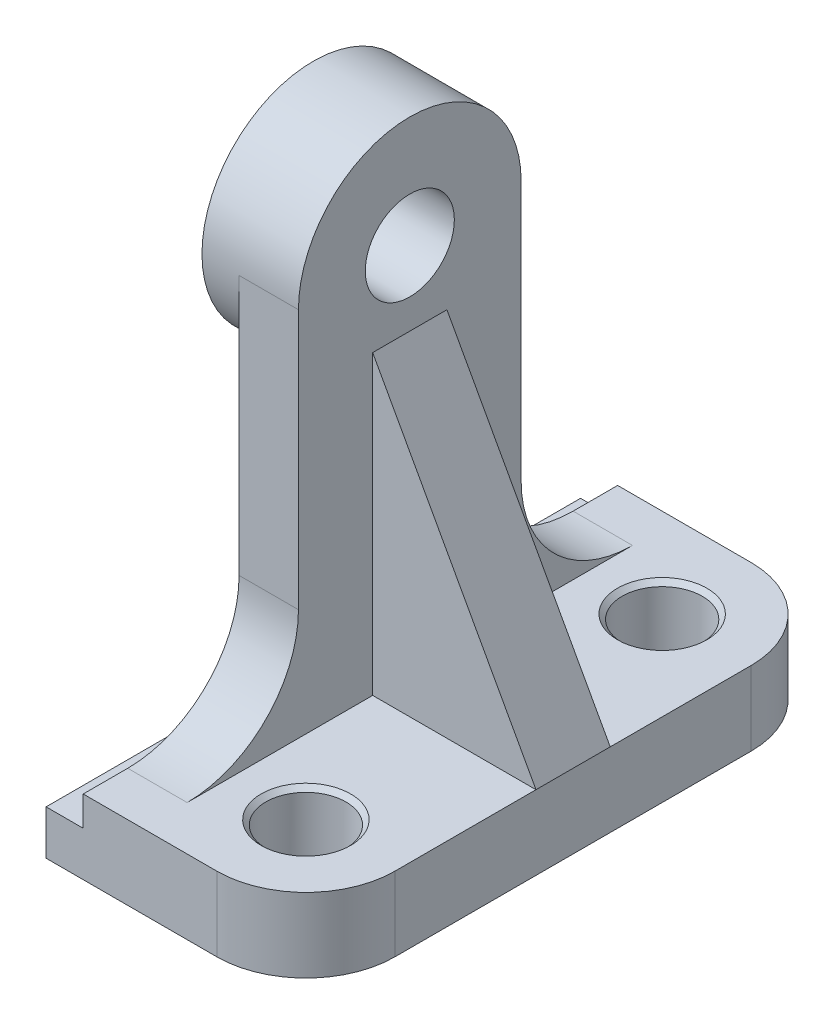
SolidWorks part; units mm, degrees
ref_plane "Front Plane" through (0, 0, 0) normal (0, 0, 1) x (1, 0, 0)
ref_plane "Top Plane" through (0, 0, 0) normal (0, 1, 0) x (1, 0, 0)
ref_plane "Right Plane" through (0, 0, 0) normal (1, 0, 0) x (0, 0, -1)
sketch "Sketch1" plane through (0, 0, 0) normal (0, 0, 1) x (1, 0, 0)
  line L0 (0, 0) -> (0, 6)
  line L1 (0, 6) -> (5, 6)
  line L2 (5, 6) -> (5, 10)
  line L3 (5, 10) -> (35, 10)
  line L4 (35, 10) -> (35, 0)
  line L5 (35, 0) -> (0, 0)
  dimension "D1" = 4
  dimension "D2" = 5
  dimension "D3" = 35
  dimension "D4" = 10
extrude "Boss-Extrude1" add sketch "Sketch1" along normal mid plane 72
sketch "Sketch2" plane through (5, 0, 0) normal (-1, 0, 0) x (0, 0, 1)
  line L0 (-15, 60) -> (-15, 10)
  line L1 (36, 10) -> (-36, 10) construction
  line L2 (-15, 10) -> (15, 10)
  line L3 (15, 10) -> (15, 60)
  arc A0 (15, 60) -> (-15, 60) centre (0, 60) ccw
  dimension "D1" = 30
  dimension "D2" = 60
extrude "Boss-Extrude2" add sketch "Sketch2" against normal blind 8
fillet "Fillet1" radius 15 2 edges at (9, 10, -15) (9, 10, 15)
sketch "Sketch3" plane through (5, 0, 0) normal (-1, 0, 0) x (0, 0, 1)
  circle A0 centre (0, 60) radius 15
  arc A1 (15, 60) -> (-15, 60) centre (0, 60) ccw construction
extrude "Boss-Extrude3" add sketch "Sketch3" along normal blind 5
hole_wizard "Hole1" positions "Sketch4" profile "Sketch5" legacy
sketch "Sketch4" plane through (13, 0, 0) normal (1, 0, 0) x (0, 0, -1)
  point P0 (0, 60)
sketch "Sketch5" plane through (13, 60, 0) normal (0, 1, 0) x (0, 0, -1)
  line L0 (0, 0) -> (0, 27.75)
  line L1 (0, 27.75) -> (6, 27.75)
  line L2 (6, 27.75) -> (6, 0)
  line L3 (6, 0) -> (0, 0)
  line L4 (0, 110) -> (0, -10) construction
  dimension "Diameter" = 12
  dimension "Depth" = 27.75
fillet "Fillet2" radius 12 2 edges at (35, 5, -36) (35, 5, 36)
hole_wizard "M12x1.25 Tapped Hole1" positions "Sketch6" profile "Sketch7" tap size "M12x1.25" standard "ANSI Metric"
sketch "Sketch6" plane through (0, 10, 0) normal (0, 1, 0) x (1, 0, 0)
  point P0 (23, -24)
  point P3 (23, 24)
sketch "Sketch7" plane through (23, 10, 24) normal (1, 0, 0) x (0, 0, 1)
  line L0 (0, 0) -> (0, 27.75)
  line L1 (0, 27.75) -> (5.4, 24.5054)
  line L2 (5.4, 24.5054) -> (5.4, 0.625)
  line L3 (5.4, 0.625) -> (6.025, 0)
  line L5 (6.025, 0) -> (0, 0)
  line L6 (-5.4, 0.625) -> (-6.025, 0) construction
  line L10 (0, 27.75) -> (-5.4, 24.5054) construction
  line L11 (0, -6.35) -> (0, 107.95) construction
  dimension "Tap Drill Dia." = 10.8
  dimension "Tap Drill Depth" = 27.75
  dimension "Near C'Sink Dia." = 12.05
  dimension "Near C'Sink Angle" = 90
  dimension "Drill Angle" = 118
cosmetic thread "Hole Thread1" parameters "D1"=24, "D2"=12
cosmetic thread "Hole Thread2" parameters "D1"=24, "D2"=12
sketch "Sketch8" plane through (0, 0, 0) normal (0, 0, 1) x (1, 0, 0)
  line L0 (35, 10) -> (13, 50)
  line L2 (35, 10) -> (23, 10) construction
  line L3 (13, 25) -> (13, 60) construction
  point P5 (0, 0)
  dimension "D1" = 40
rib "Rib1" sketch "Sketch8" sketch "Sketch8" thickness 10 extrusion direction parallel to sketch draft on no parameters "D1"=10
